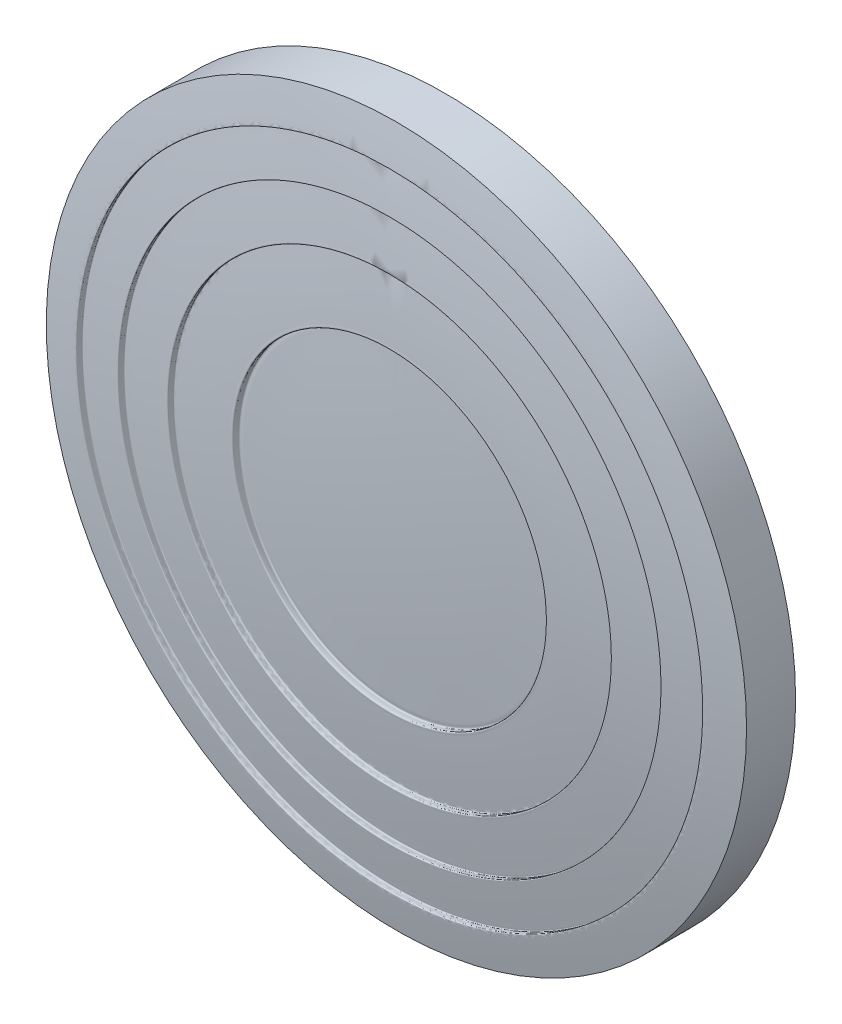
SolidWorks part; units mm, degrees
ref_plane "前视基准面" through (0, 0, 0) normal (0, 0, 1) x (1, 0, 0)
ref_plane "上视基准面" through (0, 0, 0) normal (0, 1, 0) x (1, 0, 0)
ref_plane "右视基准面" through (0, 0, 0) normal (1, 0, 0) x (0, 0, -1)
curve "曲线1"
  spline degree 3 poles (0, 0, 0.101) (0, 0.0153, 0.101) (0, 0.0459, 0.101) (0, 0.0918, 0.1009) (0, 0.1376, 0.1007) (0, 0.1835, 0.1004) (0, 0.2294, 0.1) (0, 0.2753, 0.0995) (0, 0.3212, 0.099) (0, 0.367, 0.0983) (0, 0.4129, 0.0976) (0, 0.4588, 0.0968) (0, 0.5047, 0.0959) (0, 0.5505, 0.095) (0, 0.5964, 0.0939) (0, 0.6423, 0.0928) (0, 0.6881, 0.0916) (0, 0.734, 0.0903) (0, 0.7799, 0.0889) (0, 0.8257, 0.0874) (0, 0.8716, 0.0858) (0, 0.9174, 0.0842) (0, 0.9633, 0.0825) (0, 1.0091, 0.0807) (0, 1.055, 0.0788) (0, 1.1008, 0.0768) (0, 1.1466, 0.0747) (0, 1.1925, 0.0726) (0, 1.2383, 0.0703) (0, 1.2841, 0.068) (0, 1.3299, 0.0656) (0, 1.3758, 0.0632) (0, 1.4216, 0.0606) (0, 1.4674, 0.0579) (0, 1.5132, 0.0552) (0, 1.559, 0.0524) (0, 1.6048, 0.0495) (0, 1.6505, 0.0465) (0, 1.6963, 0.0434) (0, 1.7421, 0.0403) (0, 1.7879, 0.037) (0, 1.8336, 0.0337) (0, 1.8794, 0.0303) (0, 1.9251, 0.0268) (0, 1.9709, 0.0232) (0, 2.0166, 0.0196) (0, 2.0624, 0.0158) (0, 2.1078, 0.0123) (0, 2.1547, 0.0071) (0, 2.1961, 0.0078) (0, 2.2825, -0.0224) (0, 2.211, 0.1111) (0, 2.2648, 0.0986) (0, 2.2829, 0.0978) (0, 2.3021, 0.0958) (0, 2.321, 0.0941) (0, 2.3399, 0.0923) (0, 2.3589, 0.0905) (0, 2.3778, 0.0887) (0, 2.3967, 0.0869) (0, 2.4157, 0.0851) (0, 2.4346, 0.0832) (0, 2.4535, 0.0814) (0, 2.4725, 0.0795) (0, 2.4914, 0.0776) (0, 2.5103, 0.0757) (0, 2.5293, 0.0738) (0, 2.5482, 0.0718) (0, 2.5671, 0.0699) (0, 2.5861, 0.0679) (0, 2.605, 0.066) (0, 2.6239, 0.064) (0, 2.6428, 0.062) (0, 2.6617, 0.0599) (0, 2.6807, 0.0579) (0, 2.6996, 0.0559) (0, 2.7185, 0.0538) (0, 2.7374, 0.0517) (0, 2.7563, 0.0496) (0, 2.7752, 0.0475) (0, 2.7941, 0.0454) (0, 2.813, 0.0433) (0, 2.8319, 0.0411) (0, 2.8508, 0.039) (0, 2.8697, 0.0368) (0, 2.8886, 0.0346) (0, 2.9075, 0.0324) (0, 2.9264, 0.0302) (0, 2.9453, 0.0279) (0, 2.9642, 0.0257) (0, 2.9831, 0.0234) (0, 3.002, 0.0211) (0, 3.0209, 0.0189) (0, 3.0398, 0.0165) (0, 3.0587, 0.0142) (0, 3.0776, 0.0119) (0, 3.0965, 0.0095) (0, 3.1153, 0.0072) (0, 3.1344, 0.0046) (0, 3.1523, 0.0032) (0, 3.2068, -0.0122) (0, 3.1376, 0.1112) (0, 3.1869, 0.0987) (0, 3.2008, 0.0974) (0, 3.2155, 0.0954) (0, 3.2299, 0.0935) (0, 3.2444, 0.0916) (0, 3.2589, 0.0897) (0, 3.2734, 0.0878) (0, 3.2879, 0.0859) (0, 3.3024, 0.084) (0, 3.3169, 0.0821) (0, 3.3313, 0.0801) (0, 3.3458, 0.0782) (0, 3.3603, 0.0762) (0, 3.3748, 0.0742) (0, 3.3893, 0.0723) (0, 3.4037, 0.0703) (0, 3.4182, 0.0683) (0, 3.4327, 0.0663) (0, 3.4472, 0.0643) (0, 3.4617, 0.0622) (0, 3.4761, 0.0602) (0, 3.4906, 0.0582) (0, 3.5051, 0.0561) (0, 3.5195, 0.0541) (0, 3.534, 0.052) (0, 3.5485, 0.0499) (0, 3.5629, 0.0479) (0, 3.5774, 0.0458) (0, 3.5919, 0.0437) (0, 3.6063, 0.0416) (0, 3.6208, 0.0395) (0, 3.6353, 0.0373) (0, 3.6497, 0.0352) (0, 3.6642, 0.0331) (0, 3.6786, 0.0309) (0, 3.6931, 0.0288) (0, 3.7075, 0.0266) (0, 3.722, 0.0244) (0, 3.7364, 0.0223) (0, 3.7509, 0.0201) (0, 3.7653, 0.0179) (0, 3.7798, 0.0157) (0, 3.7942, 0.0135) (0, 3.8087, 0.0112) (0, 3.8231, 0.009) (0, 3.8375, 0.0068) (0, 3.8521, 0.0044) (0, 3.866, 0.0028) (0, 3.9152, -0.0114) (0, 3.8468, 0.1114) (0, 3.8934, 0.0987) (0, 3.9052, 0.0973) (0, 3.9175, 0.0952) (0, 3.9296, 0.0933) (0, 3.9418, 0.0914) (0, 3.954, 0.0894) (0, 3.9661, 0.0875) (0, 3.9783, 0.0855) (0, 3.9905, 0.0835) (0, 4.0027, 0.0816) (0, 4.0148, 0.0796) (0, 4.027, 0.0776) (0, 4.0392, 0.0756) (0, 4.0514, 0.0736) (0, 4.0635, 0.0716) (0, 4.0757, 0.0696) (0, 4.0879, 0.0676) (0, 4.1, 0.0656) (0, 4.1122, 0.0636) (0, 4.1244, 0.0615) (0, 4.1365, 0.0595) (0, 4.1487, 0.0574) (0, 4.1609, 0.0554) (0, 4.173, 0.0533) (0, 4.1852, 0.0513) (0, 4.1973, 0.0492) (0, 4.2095, 0.0471) (0, 4.2216, 0.0451) (0, 4.2338, 0.043) (0, 4.246, 0.0409) (0, 4.2581, 0.0388) (0, 4.2703, 0.0367) (0, 4.2824, 0.0346) (0, 4.2946, 0.0325) (0, 4.3067, 0.0303) (0, 4.3189, 0.0282) (0, 4.331, 0.0261) (0, 4.3432, 0.0239) (0, 4.3553, 0.0218) (0, 4.3674, 0.0196) (0, 4.3796, 0.0175) (0, 4.3917, 0.0153) (0, 4.4039, 0.0131) (0, 4.416, 0.011) (0, 4.4282, 0.0088) (0, 4.4403, 0.0066) (0, 4.4525, 0.0043) (0, 4.4642, 0.0026) (0, 4.5108, -0.0112) (0, 4.4428, 0.1116) (0, 4.4877, 0.0988) (0, 4.498, 0.0972) (0, 4.5088, 0.0951) (0, 4.5195, 0.0932) (0, 4.5302, 0.0912) (0, 4.5409, 0.0893) (0, 4.5516, 0.0873) (0, 4.5623, 0.0853) (0, 4.573, 0.0833) (0, 4.5837, 0.0813) (0, 4.5944, 0.0793) (0, 4.6051, 0.0773) (0, 4.6157, 0.0753) (0, 4.6264, 0.0733) (0, 4.6371, 0.0713) (0, 4.6478, 0.0693) (0, 4.6585, 0.0672) (0, 4.6692, 0.0652) (0, 4.6799, 0.0632) (0, 4.6905, 0.0611) (0, 4.7012, 0.0591) (0, 4.7119, 0.057) (0, 4.7226, 0.055) (0, 4.7333, 0.0529) (0, 4.744, 0.0509) (0, 4.7546, 0.0488) (0, 4.7653, 0.0467) (0, 4.776, 0.0447) (0, 4.7867, 0.0426) (0, 4.7973, 0.0405) (0, 4.808, 0.0384) (0, 4.8187, 0.0363) (0, 4.8294, 0.0342) (0, 4.84, 0.0321) (0, 4.8507, 0.03) (0, 4.8614, 0.0279) (0, 4.872, 0.0258) (0, 4.8827, 0.0236) (0, 4.8934, 0.0215) (0, 4.904, 0.0194) (0, 4.9147, 0.0173) (0, 4.9254, 0.0151) (0, 4.936, 0.013) (0, 4.9467, 0.0108) (0, 4.9574, 0.0087) (0, 4.968, 0.0065) (0, 4.9787, 0.0043) (0, 4.9893, 0.0022) (0, 4.9964, 0.0007) (0, 5, 0) knots 0 0 0 0 0.008437 0.016874 0.025312 0.033749 0.042186 0.050623 0.05906 0.067498 0.075935 0.084372 0.092809 0.101246 0.109684 0.118121 0.126558 0.134995 0.143432 0.15187 0.160307 0.168744 0.177181 0.185618 0.194056 0.202493 0.21093 0.219367 0.227804 0.236242 0.244679 0.253116 0.261553 0.26999 0.278428 0.286865 0.295302 0.303739 0.312176 0.320614 0.329051 0.337488 0.345925 0.354362 0.3628 0.371237 0.379674 0.388111 0.396548 0.404986 0.413423 0.432 0.435498 0.438997 0.442496 0.445995 0.449494 0.452993 0.456491 0.45999 0.463489 0.466988 0.470487 0.473986 0.477484 0.480983 0.484482 0.487981 0.49148 0.494979 0.498477 0.501976 0.505475 0.508974 0.512473 0.515972 0.51947 0.522969 0.526468 0.529967 0.533466 0.536964 0.540463 0.543962 0.547461 0.55096 0.554459 0.557957 0.561456 0.564955 0.568454 0.571953 0.575452 0.57895 0.582449 0.585948 0.589447 0.592946 0.596445 0.599943 0.603442 0.622019 0.624706 0.627394 0.630081 0.632769 0.635456 0.638144 0.640831 0.643519 0.646206 0.648894 0.651582 0.654269 0.656957 0.659644 0.662332 0.665019 0.667707 0.670394 0.673082 0.675769 0.678457 0.681144 0.683832 0.686519 0.689207 0.691894 0.694582 0.697269 0.699957 0.702644 0.705332 0.708019 0.710707 0.713394 0.716082 0.718769 0.721457 0.724144 0.726832 0.729519 0.732207 0.734894 0.737582 0.740269 0.742957 0.745644 0.748332 0.751019 0.753707 0.772283 0.774551 0.776819 0.779087 0.781355 0.783623 0.785891 0.788159 0.790427 0.792695 0.794963 0.797231 0.799499 0.801767 0.804035 0.806303 0.808571 0.810839 0.813107 0.815375 0.817643 0.819911 0.822179 0.824447 0.826715 0.828983 0.831251 0.833519 0.835787 0.838055 0.840323 0.842591 0.844859 0.847127 0.849395 0.851663 0.853931 0.856199 0.858467 0.860735 0.863003 0.865271 0.867539 0.869807 0.872075 0.874343 0.876611 0.878879 0.881147 0.883415 0.901991 0.903991 0.905992 0.907992 0.909992 0.911992 0.913992 0.915993 0.917993 0.919993 0.921993 0.923993 0.925993 0.927994 0.929994 0.931994 0.933994 0.935994 0.937995 0.939995 0.941995 0.943995 0.945995 0.947995 0.949996 0.951996 0.953996 0.955996 0.957996 0.959996 0.961997 0.963997 0.965997 0.967997 0.969997 0.971998 0.973998 0.975998 0.977998 0.979998 0.981998 0.983999 0.985999 0.987999 0.989999 0.991999 0.993999 0.996 0.998 1 1 1 1
sketch "草图3" plane through (0, 0, 0) normal (1, 0, 0) x (0, 0, -1)
  line L0 (-0.2903, 0) -> (1.5199, 0) construction
  line L1 (0, 5) -> (0.701, 5)
  line L2 (0.701, 5) -> (0.701, 0)
  line L3 (-0.101, 0) -> (0.701, 0)
  spline S0 degree 3 poles (-1999.8941, -19.2459) (4.0353, -14.7511) (-0.1221, -7.3343) (-0.1006, 0.1682) (-0.0983, 0.4282) (-0.087, 0.9022) (-0.0648, 1.3759) (-0.0416, 1.7269) (-0.0315, 1.8641) (-0.0268, 1.9251) (-0.0232, 1.9709) (-0.0196, 2.0166) (-0.0158, 2.0624) (-0.0123, 2.1078) (-0.0071, 2.1547) (-0.0078, 2.1961) (0.0224, 2.2825) (-0.1111, 2.211) (-0.0986, 2.2648) (-0.0978, 2.2829) (-0.0958, 2.3021) (-0.0941, 2.321) (-0.0923, 2.3399) (-0.0881, 2.3841) (-0.0796, 2.4725) (-0.0616, 2.6492) (-0.0414, 2.832) (-0.0242, 2.9768) (-0.0173, 3.0335) (-0.0142, 3.0587) (-0.0119, 3.0776) (-0.0095, 3.0965) (-0.0072, 3.1153) (-0.0046, 3.1344) (-0.0032, 3.1523) (0.0122, 3.2068) (-0.1112, 3.1376) (-0.0987, 3.1869) (-0.0974, 3.2008) (-0.0954, 3.2155) (-0.0935, 3.2299) (-0.0916, 3.2444) (-0.0859, 3.2879) (-0.0743, 3.3748) (-0.0523, 3.534) (-0.0325, 3.669) (-0.0179, 3.7653) (-0.0142, 3.7894) (-0.0112, 3.8087) (-0.009, 3.8231) (-0.0068, 3.8375) (-0.0044, 3.8521) (-0.0028, 3.866) (0.0114, 3.9152) (-0.1114, 3.8468) (-0.0987, 3.8934) (-0.0973, 3.9052) (-0.0952, 3.9175) (-0.0933, 3.9296) (-0.0901, 3.9499) (-0.0842, 3.9864) (-0.0723, 4.0595) (-0.0515, 4.1852) (-0.0311, 4.3027) (-0.0168, 4.3836) (-0.0131, 4.4039) (-0.011, 4.416) (-0.0088, 4.4282) (-0.0066, 4.4403) (-0.0043, 4.4525) (-0.0026, 4.4642) (0.0112, 4.5108) (-0.1116, 4.4428) (-0.0988, 4.4877) (-0.0972, 4.498) (-0.0951, 4.5088) (-0.0932, 4.5195) (-0.0899, 4.5373) (-0.0833, 4.573) (-0.0693, 4.6478) (-0.0442, 4.7796) (-0.0209, 4.897) (-0.0051, 4.9751) (0.9072, 9.4599) (3.3803, 13.6193) (-1956.8142, 417.699) knots -4.071443 -4.071443 -4.071443 -4.071443 0.008437 0.016874 0.067498 0.15187 0.278428 0.329051 0.345925 0.354362 0.3628 0.371237 0.379674 0.388111 0.396548 0.404986 0.413423 0.432 0.435498 0.438997 0.442496 0.445995 0.449494 0.452993 0.470487 0.498477 0.55096 0.571953 0.57895 0.582449 0.585948 0.589447 0.592946 0.596445 0.599943 0.603442 0.622019 0.624706 0.627394 0.630081 0.632769 0.635456 0.638144 0.656957 0.683832 0.726832 0.732207 0.737582 0.740269 0.742957 0.745644 0.748332 0.751019 0.753707 0.772283 0.774551 0.776819 0.779087 0.781355 0.783623 0.790427 0.801767 0.824447 0.860735 0.867539 0.869807 0.872075 0.874343 0.876611 0.878879 0.881147 0.883415 0.901991 0.903991 0.905992 0.907992 0.909992 0.911992 0.917993 0.929994 0.953996 0.991999 0.996 0.998 3.516791 3.516791 3.516791 3.516791 only from (-0.101, 0) to (0, 5) construction
  spline S1 degree 3 poles (-0.101, 0) (-0.101, 0.0153) (-0.101, 0.0459) (-0.1006, 0.1682) (-0.0983, 0.4282) (-0.087, 0.9022) (-0.0648, 1.3759) (-0.0416, 1.7269) (-0.0315, 1.8641) (-0.0268, 1.9251) (-0.0232, 1.9709) (-0.0196, 2.0166) (-0.0158, 2.0624) (-0.0123, 2.1078) (-0.0071, 2.1547) (-0.0078, 2.1961) (0.0224, 2.2825) (-0.1111, 2.211) (-0.0986, 2.2648) (-0.0978, 2.2829) (-0.0958, 2.3021) (-0.0941, 2.321) (-0.0923, 2.3399) (-0.0881, 2.3841) (-0.0796, 2.4725) (-0.0616, 2.6492) (-0.0414, 2.832) (-0.0242, 2.9768) (-0.0173, 3.0335) (-0.0142, 3.0587) (-0.0119, 3.0776) (-0.0095, 3.0965) (-0.0072, 3.1153) (-0.0046, 3.1344) (-0.0032, 3.1523) (0.0122, 3.2068) (-0.1112, 3.1376) (-0.0987, 3.1869) (-0.0974, 3.2008) (-0.0954, 3.2155) (-0.0935, 3.2299) (-0.0916, 3.2444) (-0.0859, 3.2879) (-0.0743, 3.3748) (-0.0523, 3.534) (-0.0325, 3.669) (-0.0179, 3.7653) (-0.0142, 3.7894) (-0.0112, 3.8087) (-0.009, 3.8231) (-0.0068, 3.8375) (-0.0044, 3.8521) (-0.0028, 3.866) (0.0114, 3.9152) (-0.1114, 3.8468) (-0.0987, 3.8934) (-0.0973, 3.9052) (-0.0952, 3.9175) (-0.0933, 3.9296) (-0.0901, 3.9499) (-0.0842, 3.9864) (-0.0723, 4.0595) (-0.0515, 4.1852) (-0.0311, 4.3027) (-0.0168, 4.3836) (-0.0131, 4.4039) (-0.011, 4.416) (-0.0088, 4.4282) (-0.0066, 4.4403) (-0.0043, 4.4525) (-0.0026, 4.4642) (0.0112, 4.5108) (-0.1116, 4.4428) (-0.0988, 4.4877) (-0.0972, 4.498) (-0.0951, 4.5088) (-0.0932, 4.5195) (-0.0899, 4.5373) (-0.0833, 4.573) (-0.0693, 4.6478) (-0.0442, 4.7796) (-0.0209, 4.897) (-0.0043, 4.9787) (-0.0014, 4.9929) (0, 5) knots 0 0 0 0 0.008437 0.016874 0.067498 0.15187 0.278428 0.329051 0.345925 0.354362 0.3628 0.371237 0.379674 0.388111 0.396548 0.404986 0.413423 0.432 0.435498 0.438997 0.442496 0.445995 0.449494 0.452993 0.470487 0.498477 0.55096 0.571953 0.57895 0.582449 0.585948 0.589447 0.592946 0.596445 0.599943 0.603442 0.622019 0.624706 0.627394 0.630081 0.632769 0.635456 0.638144 0.656957 0.683832 0.726832 0.732207 0.737582 0.740269 0.742957 0.745644 0.748332 0.751019 0.753707 0.772283 0.774551 0.776819 0.779087 0.781355 0.783623 0.790427 0.801767 0.824447 0.860735 0.867539 0.869807 0.872075 0.874343 0.876611 0.878879 0.881147 0.883415 0.901991 0.903991 0.905992 0.907992 0.909992 0.911992 0.917993 0.929994 0.953996 0.991999 0.996 1 1 1 1
revolve "旋转1" add sketch "草图3" angle 360 about L0
